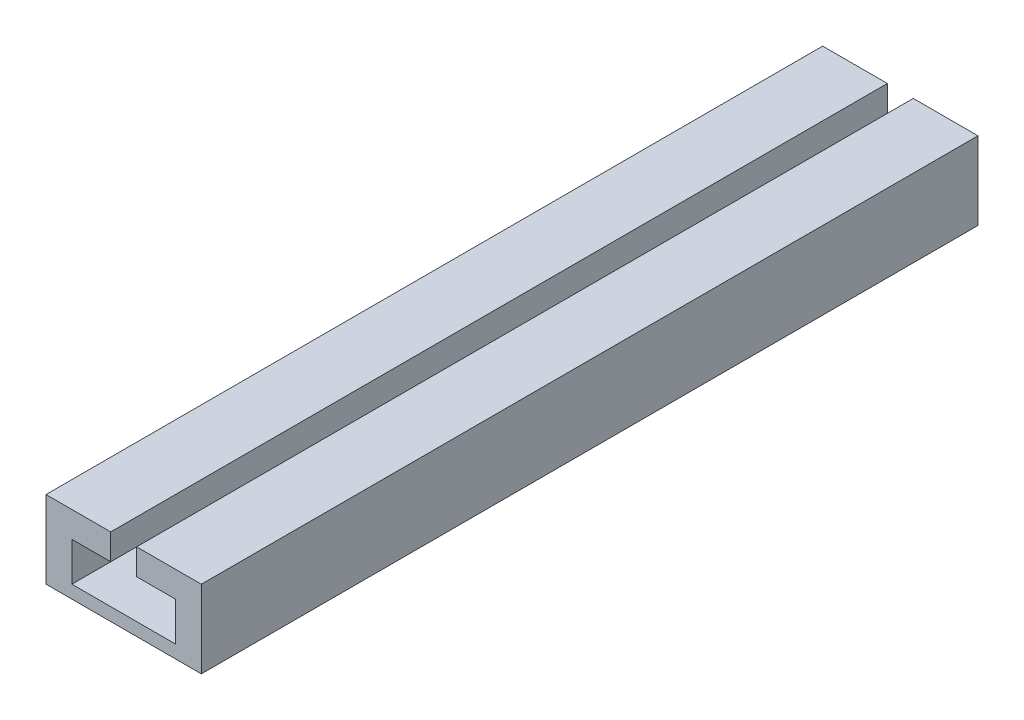
SolidWorks part; units mm, degrees
ref_plane "前基準面" through (0, 0, 0) normal (0, 0, 1) x (1, 0, 0)
ref_plane "上基準面" through (0, 0, 0) normal (0, 1, 0) x (1, 0, 0)
ref_plane "右基準面" through (0, 0, 0) normal (1, 0, 0) x (0, 0, -1)
sketch "草圖1" plane through (0, 0, 0) normal (0, 0, 1) x (1, 0, 0)
  line L1 (-3, 1.5) -> (3, 1.5)
  line L2 (-3, 1.5) -> (-3, -1.5)
  line L3 (-3, -1.5) -> (3, -1.5)
  line L4 (3, 1.5) -> (3, -1.5)
  line L5 (-3, 1.5) -> (3, -1.5) construction
  line L6 (-3, -1.5) -> (3, 1.5) construction
  point P0 (0, 0)
extrude "填料-伸長1" add sketch "草圖1" along normal blind 30 contours L1 L4 L3 L2
sketch "草圖2" plane through (0, 0, 0) normal (0, 0, -1) x (-1, 0, 0)
  line L1 (-3, 1.5) -> (-0.5, 1.5)
  line L2 (-3, 1.5) -> (-3, 0.8029)
  line L3 (-3, 0.8029) -> (-0.5, 0.8029)
  line L4 (-0.5, 1.5) -> (-0.5, 0.8029)
  line L5 (-0.5, 1.5) -> (0.5, 1.5)
  line L6 (-0.5, 1.5) -> (-0.5, 0.4816)
  line L7 (-0.5, 0.4816) -> (0.5, 0.4816)
  line L8 (0.5, 1.5) -> (0.5, 0.4816)
  point P8 (-0.6687, 0.4816)
extrude "除料-伸長2" cut sketch "草圖2" against normal blind 30 contours L6 L7 L8 L5
sketch "草圖3" plane through (0, 0, 0) normal (0, 0, -1) x (-1, 0, 0)
  line L0 (3, -1.5) -> (-3, -1.5) construction
  line L1 (-3, -1.5) -> (-2, -1.5)
  line L2 (-3, -1.5) -> (-3, 0.5)
  line L3 (-3, 0.5) -> (-2, 0.5)
  line L4 (-2, -1.5) -> (-2, 0.5)
  line L6 (-2, 0.5) -> (-2, -1.5)
  line L7 (-2, -1.5) -> (2, -1.5)
  point P9 (1.9296, 0.4555)
  point P10 (0, 0)
sketch "草圖5" plane through (0, 0, 0) normal (0, 0, -1) x (-1, 0, 0)
  line L1 (-2, 0.5) -> (2, 0.5)
  line L2 (-2, 0.5) -> (-2, -1)
  line L3 (-2, -1) -> (2, -1)
  line L4 (2, 0.5) -> (2, -1)
extrude "除料-伸長5" cut sketch "草圖5" against normal blind 30 contours L3 L4 L1 L2
